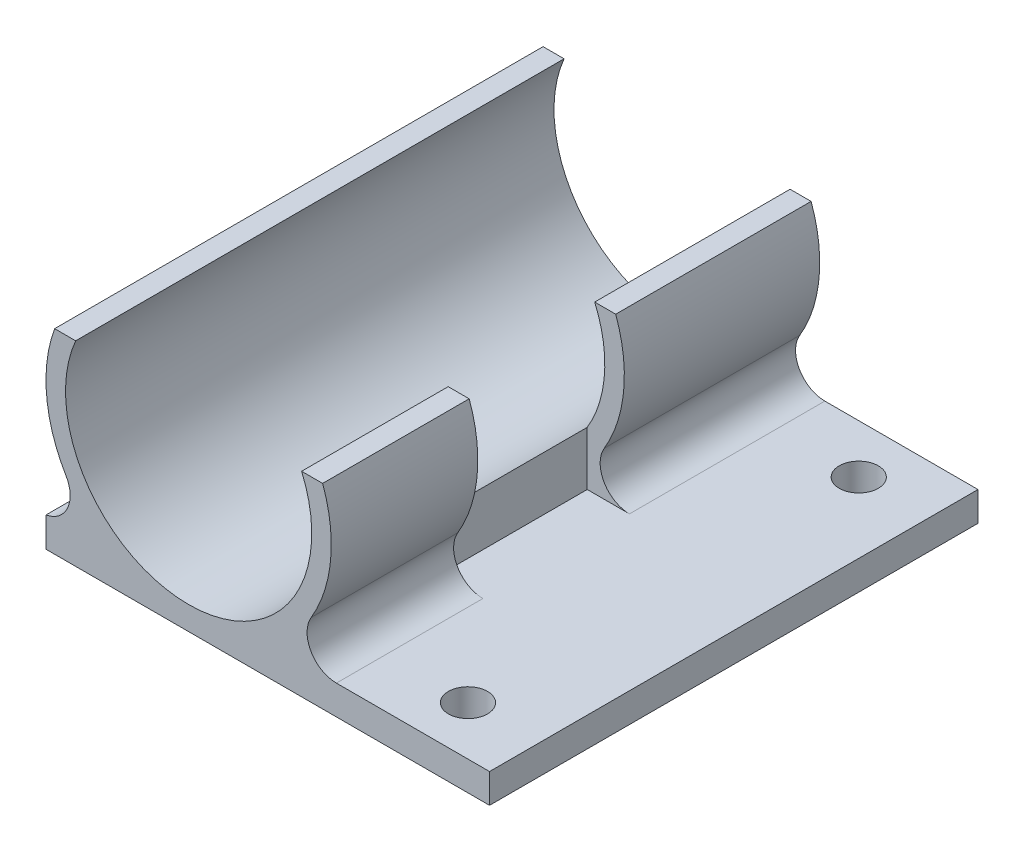
SolidWorks part; units mm, degrees
ref_plane "Front Plane" through (0, 0, 0) normal (0, 0, 1) x (1, 0, 0)
ref_plane "Top Plane" through (0, 0, 0) normal (0, 1, 0) x (1, 0, 0)
ref_plane "Right Plane" through (0, 0, 0) normal (1, 0, 0) x (0, 0, -1)
sketch "Sketch1" plane through (0, 0, 0) normal (0, 0, 1) x (1, 0, 0)
  line L0 (34.0655, 5) -> (36.2171, 5)
  line L1 (8.7829, 5) -> (10.9345, 5)
  line L3 (7.9, -15) -> (53.3012, -15)
  line L4 (53.3012, -12) -> (53.3012, -15)
  line L6 (7.9, -11.9537) -> (7.9, -15)
  line L7 (37.6248, -12) -> (53.3012, -12)
  arc A0 (10.9345, 5) -> (34.0655, 5) centre (22.5, 0) ccw
  arc A1 (8.7829, 5) -> (9.9533, -7.4659) centre (22.5, 0) ccw
  arc A2 (35.0467, -7.4659) -> (36.2171, 5) centre (22.5, 0) ccw
  arc A5 (37.6248, -12) -> (35.0467, -7.4659) centre (37.6248, -9) cw
  arc A6 (7.9, -11.9537) -> (9.9533, -7.4659) centre (7.3752, -9) ccw
  point P9 (22.5, 0)
  point P10 (34.5494, 3.6839)
  point P11 (37.1, 0)
  point P19 (30.8162, -12)
  dimension "D1" = 3
extrude "Boss-Extrude1" add sketch "Sketch1" along normal blind 50
sketch "Sketch2" plane through (53.3012, 0, 0) normal (1, 0, 0) x (0, 0, -1)
  line L0 (-50, -12) -> (0, -12) construction
  line L1 (-35, -12) -> (-20, -12)
  line L2 (-35, -12) -> (-35, 8.4363)
  line L3 (-35, 8.4363) -> (-20, 8.4363)
  line L4 (-20, -12) -> (-20, 8.4363)
  line L5 (-50, 0) -> (-50, -7.4659) construction
  dimension "D1" = 15
  dimension "D2" = 15
extrude "Cut-Extrude1" cut sketch "Sketch2" against normal blind 20
sketch "Sketch3" plane through (0, -12, 0) normal (0, 1, 0) x (1, 0, 0)
  line L0 (53.3012, -50) -> (37.6248, -50) construction
  circle A0 centre (46.0948, -45) radius 2
  circle A1 centre (46.0948, -5) radius 2
  dimension "D1" = 5
  dimension "D2" = 40
extrude "Cut-Extrude2" cut sketch "Sketch3" against normal through all
